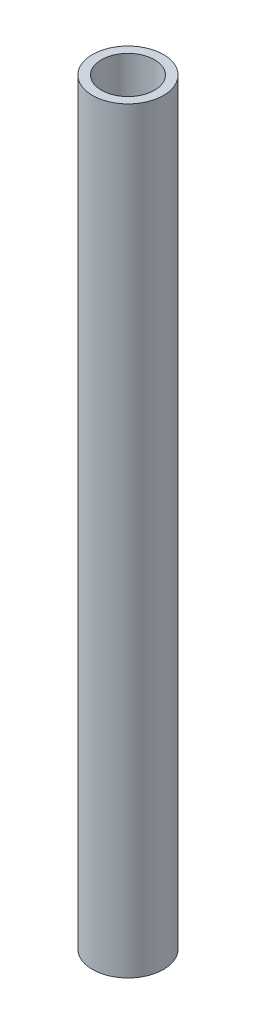
SolidWorks part; units mm, degrees
ref_plane "Front Plane" through (0, 0, 0) normal (0, 0, 1) x (1, 0, 0)
ref_plane "Top Plane" through (0, 0, 0) normal (0, 1, 0) x (1, 0, 0)
ref_plane "Right Plane" through (0, 0, 0) normal (1, 0, 0) x (0, 0, -1)
sketch "Sketch1" plane through (0, 0, 0) normal (0, 1, 0) x (1, 0, 0)
  circle A0 centre (0, 0) radius 7.112
  circle A1 centre (0, 0) radius 9.525
  point P5 (0, -0.0292)
  dimension "D1" = 2.413
  dimension "D2" = 19.05
extrude "Boss-Extrude1" add sketch "Sketch1" along normal blind 203.2
